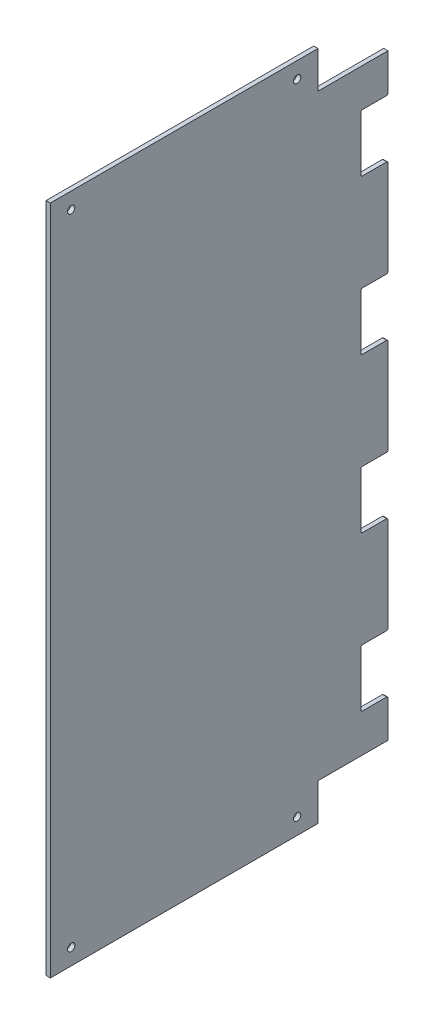
SolidWorks part; units mm, degrees
ref_plane "Front Plane" through (0, 0, 0) normal (1, 0, 0) x (0, 1, 0)
ref_plane "Top Plane" through (0, 0, 0) normal (0, 0, 1) x (0, 1, 0)
ref_plane "Right Plane" through (0, 0, 0) normal (0, 1, 0) x (-1, 0, 0)
sketch "Sketch1" plane through (0, 0, 0) normal (1, 0, 0) x (0, 1, 0)
  line L0 (0, 0) -> (0, 100) construction
  line L1 (-250, -100) -> (250, -100)
  line L2 (-250, -100) -> (-250, 100)
  line L3 (-250, 100) -> (250, 100)
  line L4 (250, -100) -> (250, 100)
  line L5 (-250, -100) -> (250, 100) construction
  line L6 (-250, 100) -> (250, -100) construction
  line L7 (0, 0) -> (250, 0) construction
  circle A0 centre (-237.5, 84) radius 2.75
  circle A1 centre (237.5, 84) radius 2.75
  circle A2 centre (237.5, -84) radius 2.75
  circle A3 centre (-237.5, -84) radius 2.75
  point P0 (0, 0)
  dimension "D3" = 5.5
  dimension "D1" = 200
  dimension "D2" = 500
  dimension "D4" = 12.5
  dimension "D5" = 16
extrude "Boss-Extrude1" add sketch "Sketch1" along normal blind 3.175 contours L1 L4 L3 L2 A1 A0 A2 A3
sketch "Sketch2" plane through (3.175, 0, 0) normal (1, 0, 0) x (0, 1, 0)
  line L0 (-250, 100) -> (250, 100) construction
  line L1 (249.5, -99.5) -> (-249.5, -99.5)
  line L2 (249.5, -99.5) -> (249.5, 99.5)
  line L3 (249.5, 99.5) -> (-249.5, 99.5)
  line L4 (-249.5, -99.5) -> (-249.5, 99.5)
  line L5 (249.5, -99.5) -> (-249.5, 99.5) construction
  line L6 (249.5, 99.5) -> (-249.5, -99.5) construction
  line L7 (-250, -100) -> (-250, 100) construction
  line L9 (250, -100) -> (-250, -100)
  line L10 (250, -100) -> (250, 100)
  line L11 (250, 100) -> (-250, 100)
  line L12 (-250, -100) -> (-250, 100)
  line L13 (250, -100) -> (-250, 100) construction
  line L14 (250, 100) -> (-250, -100) construction
  point P0 (0, 0)
  point P10 (0, 0)
  dimension "D1" = 0.5
  dimension "D2" = 0.5
extrude "Cut-Extrude1" cut sketch "Sketch2" against normal blind 3.175
sketch "Sketch3" plane through (3.175, 0, 0) normal (1, 0, 0) x (0, 1, 0)
  line L0 (249.5, -99.5) -> (249.5, 99.5) construction
  line L1 (-249.5, -99.5) -> (249.5, -99.5)
  line L2 (-249.5, -99.5) -> (-249.5, -151.5)
  line L3 (-249.5, -151.5) -> (249.5, -151.5)
  line L4 (249.5, -99.5) -> (249.5, -151.5)
  line L5 (-249.5, -99.5) -> (249.5, -151.5) construction
  line L6 (-249.5, -151.5) -> (249.5, -99.5) construction
  line L7 (-249.5, -99.5) -> (249.5, -99.5) construction
  line L8 (0, -125.5) -> (0, -151.5) construction
  line L9 (188.6, -151.5) -> (155.9, -151.5) construction
  line L10 (188.6, -151.5) -> (188.6, -136.5) construction
  line L11 (188.6, -136.5) -> (155.9, -136.5) construction
  line L12 (155.9, -151.5) -> (155.9, -136.5) construction
  line L13 (188.6, -151.5) -> (155.9, -136.5) construction
  line L14 (188.6, -136.5) -> (155.9, -151.5) construction
  line L15 (73.77, -151.5) -> (41.07, -151.5) construction
  line L16 (73.77, -151.5) -> (73.77, -136.5) construction
  line L17 (73.77, -136.5) -> (41.07, -136.5) construction
  line L18 (41.07, -151.5) -> (41.07, -136.5) construction
  line L19 (73.77, -151.5) -> (41.07, -136.5) construction
  line L20 (73.77, -136.5) -> (41.07, -151.5) construction
  line L21 (-188.6, -136.5) -> (-155.9, -136.5) construction
  line L22 (-155.9, -151.5) -> (-155.9, -136.5) construction
  line L23 (-188.6, -151.5) -> (-155.9, -151.5) construction
  line L24 (-188.6, -151.5) -> (-188.6, -136.5) construction
  line L25 (-73.77, -136.5) -> (-41.07, -136.5) construction
  line L26 (-41.07, -151.5) -> (-41.07, -136.5) construction
  line L27 (-73.77, -151.5) -> (-41.07, -151.5) construction
  line L28 (-73.77, -151.5) -> (-73.77, -136.5) construction
  line L29 (-193.6, -151.5) -> (-193.6, -131.5)
  line L30 (-193.6, -131.5) -> (-150.9, -131.5)
  line L31 (-150.9, -151.5) -> (-150.9, -131.5)
  line L32 (-78.77, -151.5) -> (-78.77, -131.5)
  line L33 (-78.77, -131.5) -> (-36.07, -131.5)
  line L34 (-36.07, -151.5) -> (-36.07, -131.5)
  line L35 (193.6, -151.5) -> (193.6, -131.5)
  line L36 (193.6, -131.5) -> (150.9, -131.5)
  line L37 (150.9, -151.5) -> (150.9, -131.5)
  line L38 (78.77, -151.5) -> (78.77, -131.5)
  line L39 (78.77, -131.5) -> (36.07, -131.5)
  line L40 (36.07, -151.5) -> (36.07, -131.5)
  line L42 (249.5, -151.5) -> (222, -151.5)
  line L43 (249.5, -151.5) -> (249.5, -99.5)
  line L44 (249.5, -99.5) -> (222, -99.5)
  line L45 (222, -151.5) -> (222, -99.5)
  line L46 (249.5, -151.5) -> (222, -99.5) construction
  line L47 (249.5, -99.5) -> (222, -151.5) construction
  line L48 (-249.5, -151.5) -> (-222, -151.5)
  line L49 (-249.5, -151.5) -> (-249.5, -99.5)
  line L50 (-249.5, -99.5) -> (-222, -99.5)
  line L51 (-222, -151.5) -> (-222, -99.5)
  line L52 (-249.5, -151.5) -> (-222, -99.5) construction
  line L53 (-249.5, -99.5) -> (-222, -151.5) construction
  point P4 (0, -125.5)
  point P15 (172.25, -144)
  point P19 (57.42, -144)
  point P50 (235.75, -125.5)
  point P54 (-235.75, -125.5)
  point P55 (231.2521, -99.5)
  line M28 (-249.5, -99.5) -> (249.5, -99.5)
  dimension "D1" = 15
  dimension "D2" = 32.7
  dimension "D3" = 60.9
  dimension "D4" = 52
  dimension "D5" = 82.13
  dimension "D6" = 15
  dimension "D7" = 32.7
  dimension "D10" = 27.5
  dimension "D11" = 52
  dimension "D12" = 27.5
  dimension "D8" = 5
  dimension "D9" = 5
extrude "Boss-Extrude2" add sketch "Sketch3" against normal through all contours L3 L40 L39 L38 L37 L36 L35 L4 L2 L29 L30 L31 L32 L33 L34 M28
fillet "Fillet1" radius 1 16 edges at (1.5875, -78.77, -131.5) (1.5875, 36.07, -131.5) (1.5875, 150.9, -131.5) (1.5875, 150.9, -151.5) (1.5875, 193.6, -151.5) (1.5875, 193.6, -131.5) (1.5875, -78.77, -151.5) (1.5875, 36.07, -151.5) (1.5875, 78.77, -151.5) (1.5875, 78.77, -131.5) (1.5875, -36.07, -131.5) (1.5875, -36.07, -151.5) (1.5875, -150.9, -131.5) (1.5875, -150.9, -151.5) (1.5875, -193.6, -151.5) (1.5875, -193.6, -131.5)
